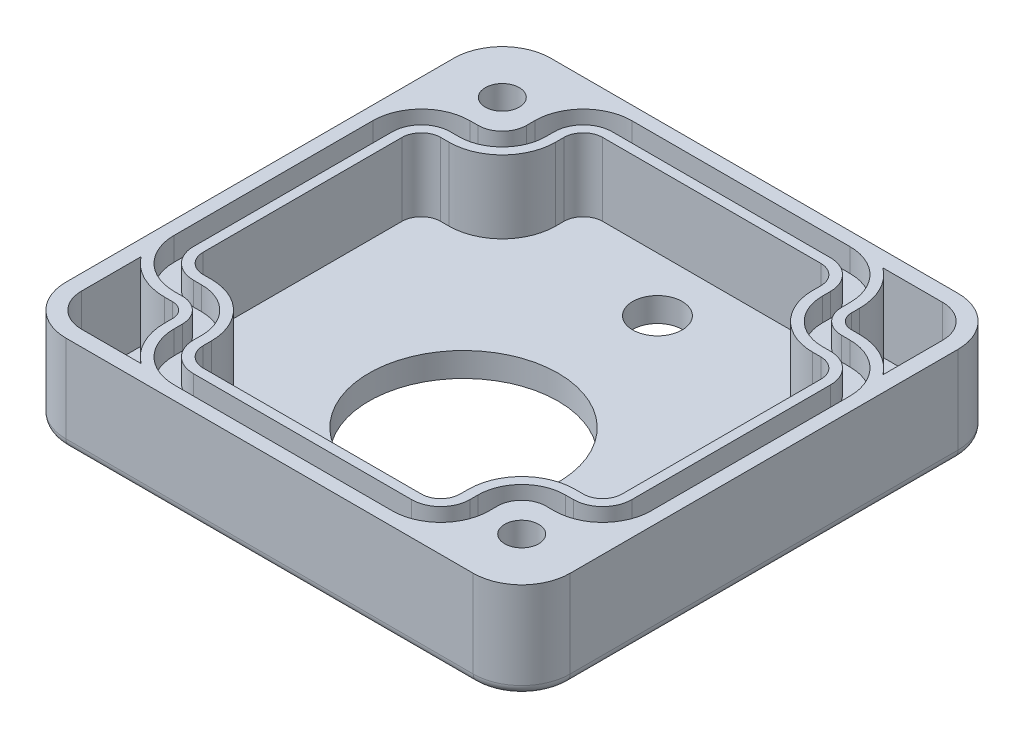
SolidWorks part; units mm, degrees
ref_plane "Спереди" through (0, 0, 0) normal (0, 0, 1) x (1, 0, 0)
ref_plane "Сверху" through (0, 0, 0) normal (0, 1, 0) x (1, 0, 0)
ref_plane "Справа" through (0, 0, 0) normal (1, 0, 0) x (0, 0, -1)
sketch "Эскиз1" plane through (0, 0, 0) normal (0, 1, 0) x (1, 0, 0)
  line L1 (-21, 25) -> (21, 25)
  line L2 (-26, 20) -> (-26, -20)
  line L3 (-21, -25) -> (21, -25)
  line L4 (26, 20) -> (26, -20)
  line L5 (-26, 25) -> (26, -25) construction
  line L6 (-26, -25) -> (26, 25) construction
  arc A0 (21, 25) -> (26, 20) centre (21, 20) cw
  arc A1 (26, -20) -> (21, -25) centre (21, -20) cw
  arc A2 (-21, -25) -> (-26, -20) centre (-21, -20) cw
  arc A3 (-26, 20) -> (-21, 25) centre (-21, 20) cw
  point P0 (0, 0)
  dimension "D3" = 5
  dimension "D1" = 52
  dimension "D2" = 50
sketch "Эскиз2" plane through (0, 0, 0) normal (0, 1, 0) x (1, 0, 0)
  line L0 (-13.25, 18.6) -> (-13.25, 17.75)
  line L1 (-18.75, 12.25) -> (-19.6, 12.25)
  line L2 (-21.6, 10.25) -> (-21.6, -10.25)
  line L3 (-19.6, -12.25) -> (-18.75, -12.25)
  line L4 (-13.25, -17.75) -> (-13.25, -18.6)
  line L5 (-11.25, -20.6) -> (11.25, -20.6)
  line L6 (13.25, -18.6) -> (13.25, -17.75)
  line L7 (18.75, -12.25) -> (19.6, -12.25)
  line L8 (21.6, -10.25) -> (21.6, 10.25)
  line L9 (19.6, 12.25) -> (18.75, 12.25)
  line L10 (13.25, 17.75) -> (13.25, 18.6)
  line L11 (11.25, 20.6) -> (-11.25, 20.6)
  line L12 (-21, 25) -> (21, 25) construction
  line L13 (-21, -25) -> (21, -25) construction
  line L14 (-26, 20) -> (-26, -20) construction
  line L15 (26, 20) -> (26, -20) construction
  arc A0 (-13.25, 18.6) -> (-11.25, 20.6) centre (-11.25, 18.6) cw
  arc A1 (13.25, 18.6) -> (11.25, 20.6) centre (11.25, 18.6) ccw
  arc A2 (21.6, 10.25) -> (19.6, 12.25) centre (19.6, 10.25) ccw
  arc A3 (21.6, -10.25) -> (19.6, -12.25) centre (19.6, -10.25) cw
  arc A4 (13.25, -18.6) -> (11.25, -20.6) centre (11.25, -18.6) cw
  arc A5 (-11.25, -20.6) -> (-13.25, -18.6) centre (-11.25, -18.6) cw
  arc A6 (-19.6, -12.25) -> (-21.6, -10.25) centre (-19.6, -10.25) cw
  arc A7 (-21.6, 10.25) -> (-19.6, 12.25) centre (-19.6, 10.25) cw
  arc A8 (-18.75, -12.25) -> (-13.25, -17.75) centre (-18.75, -17.75) cw
  arc A9 (13.25, -17.75) -> (18.75, -12.25) centre (18.75, -17.75) cw
  arc A10 (18.75, 12.25) -> (13.25, 17.75) centre (18.75, 17.75) cw
  arc A11 (-18.75, 12.25) -> (-13.25, 17.75) centre (-18.75, 17.75) ccw
  point P3 (0, 20.6)
  point P13 (-21.6, 0)
  point P14 (0, -20.6)
  point P15 (21.6, 0)
  dimension "D7" = 2
  dimension "D8" = 5.5
  dimension "D1" = 4.4
  dimension "D2" = 4.4
  dimension "D3" = 4.4
  dimension "D4" = 4.4
  dimension "D5" = 26.5
  dimension "D9" = 24.5
extrude "Бобышка-Вытянуть1" add sketch "Эскиз1" along normal blind 10
extrude "Вырез-Вытянуть1" cut sketch "Эскиз2" along normal up to surface (7.5 mm away) from offset 2.5 up to face at (0, 10, 0)
sketch "Эскиз4" plane through (0, 0, 0) normal (0, 1, 0) x (1, 0, 0)
  line L8 (-25.5, 20) -> (-25.5, -20)
  line L9 (-21, -24.5) -> (21, -24.5)
  line L10 (25.5, -20) -> (25.5, 20)
  line L11 (21, 24.5) -> (-21, 24.5)
  line L12 (-25.5, 20) -> (-25.5, -20)
  line L13 (-21, -24.5) -> (21, -24.5)
  line L14 (25.5, -20) -> (25.5, 20)
  line L15 (21, 24.5) -> (-21, 24.5)
  arc A8 (-25.5, -20) -> (-21, -24.5) centre (-21, -20) ccw
  arc A9 (21, -24.5) -> (25.5, -20) centre (21, -20) ccw
  arc A10 (25.5, 20) -> (21, 24.5) centre (21, 20) ccw
  arc A11 (-21, 24.5) -> (-25.5, 20) centre (-21, 20) ccw
  arc A12 (-25.5, -20) -> (-21, -24.5) centre (-21, -20) ccw
  arc A13 (21, -24.5) -> (25.5, -20) centre (21, -20) ccw
  arc A14 (25.5, 20) -> (21, 24.5) centre (21, 20) ccw
  arc A15 (-21, 24.5) -> (-25.5, 20) centre (-21, 20) ccw
  dimension "D1" = 0.5
sketch "Эскиз5" plane through (0, 0, 0) normal (0, 1, 0) x (1, 0, 0)
  line L0 (-16.25, 18.6) -> (-16.25, 17.75)
  line L1 (-18.75, 15.25) -> (-19.6, 15.25)
  line L2 (-24.6, 10.25) -> (-24.6, -10.25)
  line L3 (-19.6, -15.25) -> (-18.75, -15.25)
  line L4 (-16.25, -17.75) -> (-16.25, -18.6)
  line L5 (-11.25, -23.6) -> (11.25, -23.6)
  line L6 (16.25, -18.6) -> (16.25, -17.75)
  line L7 (18.75, -15.25) -> (19.6, -15.25)
  line L8 (24.6, -10.25) -> (24.6, 10.25)
  line L9 (19.6, 15.25) -> (18.75, 15.25)
  line L10 (16.25, 17.75) -> (16.25, 18.6)
  line L11 (11.25, 23.6) -> (-11.25, 23.6)
  line L24 (-14.25, 18.6) -> (-14.25, 17.75)
  line L25 (-18.75, 13.25) -> (-19.6, 13.25)
  line L26 (-22.6, 10.25) -> (-22.6, -10.25)
  line L27 (-19.6, -13.25) -> (-18.75, -13.25)
  line L28 (-14.25, -17.75) -> (-14.25, -18.6)
  line L29 (-11.25, -21.6) -> (11.25, -21.6)
  line L30 (14.25, -18.6) -> (14.25, -17.75)
  line L31 (18.75, -13.25) -> (19.6, -13.25)
  line L32 (22.6, -10.25) -> (22.6, 10.25)
  line L33 (19.6, 13.25) -> (18.75, 13.25)
  line L34 (14.25, 17.75) -> (14.25, 18.6)
  line L35 (11.25, 21.6) -> (-11.25, 21.6)
  line L36 (-14.25, 18.6) -> (-14.25, 17.75)
  line L37 (-18.75, 13.25) -> (-19.6, 13.25)
  line L38 (-22.6, 10.25) -> (-22.6, -10.25)
  line L39 (-19.6, -13.25) -> (-18.75, -13.25)
  line L40 (-14.25, -17.75) -> (-14.25, -18.6)
  line L41 (-11.25, -21.6) -> (11.25, -21.6)
  line L42 (14.25, -18.6) -> (14.25, -17.75)
  line L43 (18.75, -13.25) -> (19.6, -13.25)
  line L44 (22.6, -10.25) -> (22.6, 10.25)
  line L45 (19.6, 13.25) -> (18.75, 13.25)
  line L46 (14.25, 17.75) -> (14.25, 18.6)
  line L47 (11.25, 21.6) -> (-11.25, 21.6)
  arc A0 (-11.25, 23.6) -> (-16.25, 18.6) centre (-11.25, 18.6) ccw
  arc A1 (-18.75, 15.25) -> (-16.25, 17.75) centre (-18.75, 17.75) ccw
  arc A2 (-19.6, 15.25) -> (-24.6, 10.25) centre (-19.6, 10.25) ccw
  arc A3 (-24.6, -10.25) -> (-19.6, -15.25) centre (-19.6, -10.25) ccw
  arc A4 (-16.25, -17.75) -> (-18.75, -15.25) centre (-18.75, -17.75) ccw
  arc A5 (-16.25, -18.6) -> (-11.25, -23.6) centre (-11.25, -18.6) ccw
  arc A6 (11.25, -23.6) -> (16.25, -18.6) centre (11.25, -18.6) ccw
  arc A7 (18.75, -15.25) -> (16.25, -17.75) centre (18.75, -17.75) ccw
  arc A8 (19.6, -15.25) -> (24.6, -10.25) centre (19.6, -10.25) ccw
  arc A9 (24.6, 10.25) -> (19.6, 15.25) centre (19.6, 10.25) ccw
  arc A10 (16.25, 17.75) -> (18.75, 15.25) centre (18.75, 17.75) ccw
  arc A11 (16.25, 18.6) -> (11.25, 23.6) centre (11.25, 18.6) ccw
  arc A24 (-18.75, 13.25) -> (-14.25, 17.75) centre (-18.75, 17.75) ccw
  arc A25 (-19.6, 13.25) -> (-22.6, 10.25) centre (-19.6, 10.25) ccw
  arc A26 (-22.6, -10.25) -> (-19.6, -13.25) centre (-19.6, -10.25) ccw
  arc A27 (-14.25, -17.75) -> (-18.75, -13.25) centre (-18.75, -17.75) ccw
  arc A28 (-14.25, -18.6) -> (-11.25, -21.6) centre (-11.25, -18.6) ccw
  arc A29 (11.25, -21.6) -> (14.25, -18.6) centre (11.25, -18.6) ccw
  arc A30 (18.75, -13.25) -> (14.25, -17.75) centre (18.75, -17.75) ccw
  arc A31 (19.6, -13.25) -> (22.6, -10.25) centre (19.6, -10.25) ccw
  arc A32 (22.6, 10.25) -> (19.6, 13.25) centre (19.6, 10.25) ccw
  arc A33 (14.25, 17.75) -> (18.75, 13.25) centre (18.75, 17.75) ccw
  arc A34 (14.25, 18.6) -> (11.25, 21.6) centre (11.25, 18.6) ccw
  arc A35 (-11.25, 21.6) -> (-14.25, 18.6) centre (-11.25, 18.6) ccw
  arc A36 (-18.75, 13.25) -> (-14.25, 17.75) centre (-18.75, 17.75) ccw
  arc A37 (-19.6, 13.25) -> (-22.6, 10.25) centre (-19.6, 10.25) ccw
  arc A38 (-22.6, -10.25) -> (-19.6, -13.25) centre (-19.6, -10.25) ccw
  arc A39 (-14.25, -17.75) -> (-18.75, -13.25) centre (-18.75, -17.75) ccw
  arc A40 (-14.25, -18.6) -> (-11.25, -21.6) centre (-11.25, -18.6) ccw
  arc A41 (11.25, -21.6) -> (14.25, -18.6) centre (11.25, -18.6) ccw
  arc A42 (18.75, -13.25) -> (14.25, -17.75) centre (18.75, -17.75) ccw
  arc A43 (19.6, -13.25) -> (22.6, -10.25) centre (19.6, -10.25) ccw
  arc A44 (22.6, 10.25) -> (19.6, 13.25) centre (19.6, 10.25) ccw
  arc A45 (14.25, 17.75) -> (18.75, 13.25) centre (18.75, 17.75) ccw
  arc A46 (14.25, 18.6) -> (11.25, 21.6) centre (11.25, 18.6) ccw
  arc A47 (-11.25, 21.6) -> (-14.25, 18.6) centre (-11.25, 18.6) ccw
  dimension "D1" = 1
  dimension "D2" = 2
extrude "Вырез-Вытянуть7" cut sketch "Эскиз5" against normal blind 2.4 from surface at 10 starting at face at (0, 10, 0)
sketch "Эскиз14" plane through (0, 0, 0) normal (0, 1, 0) x (1, 0, 0)
  line L10 (21, 23.4) -> (-21, 23.4)
  line L11 (24.4, -20) -> (24.4, 20)
  line L12 (-21, -23.4) -> (21, -23.4)
  line L13 (-24.4, 20) -> (-24.4, -20)
  line L14 (21, 23.4) -> (14.85, 23.4)
  line L15 (24.4, 13.85) -> (24.4, 20)
  line L16 (-21, -23.4) -> (-14.85, -23.4)
  line L17 (-24.4, -13.85) -> (-24.4, -20)
  line L18 (-17.25, -17.75) -> (-17.25, -18.6)
  line L19 (-19.6, -16.25) -> (-18.75, -16.25)
  line L20 (-17.25, -17.75) -> (-17.25, -18.6)
  line L21 (-19.6, -16.25) -> (-18.75, -16.25)
  line L24 (19.6, 16.25) -> (18.75, 16.25)
  line L25 (17.25, 17.75) -> (17.25, 18.6)
  line L26 (19.6, 16.25) -> (18.75, 16.25)
  line L27 (17.25, 17.75) -> (17.25, 18.6)
  arc A9 (24.4, 20) -> (21, 23.4) centre (21, 20) ccw
  arc A10 (21, -23.4) -> (24.4, -20) centre (21, -20) ccw
  arc A11 (-24.4, -20) -> (-21, -23.4) centre (-21, -20) ccw
  arc A12 (-21, 23.4) -> (-24.4, 20) centre (-21, 20) ccw
  arc A13 (24.4, 20) -> (21, 23.4) centre (21, 20) ccw
  arc A15 (-24.4, -20) -> (-21, -23.4) centre (-21, -20) ccw
  arc A19 (-17.25, -18.6) -> (-11.25, -24.6) centre (-11.25, -18.6) ccw
  arc A20 (-17.25, -17.75) -> (-18.75, -16.25) centre (-18.75, -17.75) ccw
  arc A21 (-25.6, -10.25) -> (-19.6, -16.25) centre (-19.6, -10.25) ccw
  arc A22 (-17.25, -18.6) -> (-14.85, -23.4) centre (-11.25, -18.6) ccw
  arc A23 (-17.25, -17.75) -> (-18.75, -16.25) centre (-18.75, -17.75) ccw
  arc A24 (-24.4, -13.85) -> (-19.6, -16.25) centre (-19.6, -10.25) ccw
  arc A28 (25.6, 10.25) -> (19.6, 16.25) centre (19.6, 10.25) ccw
  arc A29 (17.25, 17.75) -> (18.75, 16.25) centre (18.75, 17.75) ccw
  arc A30 (17.25, 18.6) -> (11.25, 24.6) centre (11.25, 18.6) ccw
  arc A31 (24.4, 13.85) -> (19.6, 16.25) centre (19.6, 10.25) ccw
  arc A32 (17.25, 17.75) -> (18.75, 16.25) centre (18.75, 17.75) ccw
  arc A33 (17.25, 18.6) -> (14.85, 23.4) centre (11.25, 18.6) ccw
  dimension "D1" = 1.6
  dimension "D2" = 1
  dimension "D3" = 1
extrude "Вырез-Вытянуть9" cut sketch "Эскиз14" along normal up to surface (8 mm away) from offset 2 up to face at (0, 10, 0)
sketch "Эскиз15" plane through (0, 0, 0) normal (0, 1, 0) x (1, 0, 0)
  line L1 (-20, 19) -> (20, 19) construction
  line L2 (-20, 19) -> (-20, -19) construction
  line L3 (-20, -19) -> (20, -19) construction
  line L4 (20, 19) -> (20, -19) construction
  line L5 (-20, 19) -> (20, -19) construction
  line L6 (-20, -19) -> (20, 19) construction
  circle A0 centre (-20, 19) radius 1.75
  circle A1 centre (20, -19) radius 1.75
  point P0 (0, 0)
  dimension "D3" = 3.5
  dimension "D1" = 38
  dimension "D2" = 40
extrude "Вырез-Вытянуть10" cut sketch "Эскиз15" along normal up to surface (10 mm away) up to face at (-19.8429, 10, 18.8429)
sketch "Эскиз16" plane through (0, 0, 0) normal (0, 1, 0) x (1, 0, 0)
  circle A0 centre (-20, 19) radius 2.35
  circle A1 centre (20, -19) radius 2.35
  dimension "D1" = 4.7
extrude "Вырез-Вытянуть11" cut sketch "Эскиз16" along normal blind 6
sketch "Эскиз17" plane through (0, 0, 0) normal (0, 1, 0) x (1, 0, 0)
  circle A0 centre (-20, 19) radius 4
  circle A1 centre (20, -19) radius 4
  dimension "D1" = 8
extrude "Вырез-Вытянуть12" cut sketch "Эскиз17" along normal blind 3
fillet "Скругление2" radius 1 8 edges at (24.5355, 0, -23.5355) (26, 0, 0) (24.5355, 0, 23.5355) (0, 0, 25) (-24.5355, 0, 23.5355) (-26, 0, 0) (-24.5355, 0, -23.5355) (0, 0, -25)
sketch "Эскиз18" plane through (0, 0, 0) normal (0, 1, 0) x (1, 0, 0)
  line L1 (-21, 25) -> (21, 25) construction
  line L2 (-21, -25) -> (21, -25) construction
  circle A0 centre (0, -5) radius 9.75
  circle A1 centre (0, 15) radius 2.55
  dimension "D1" = 19.5
  dimension "D3" = 5.1
  dimension "D2" = 20
  dimension "D6" = 10
extrude "Вырез-Вытянуть13" cut sketch "Эскиз18" along normal blind 10
